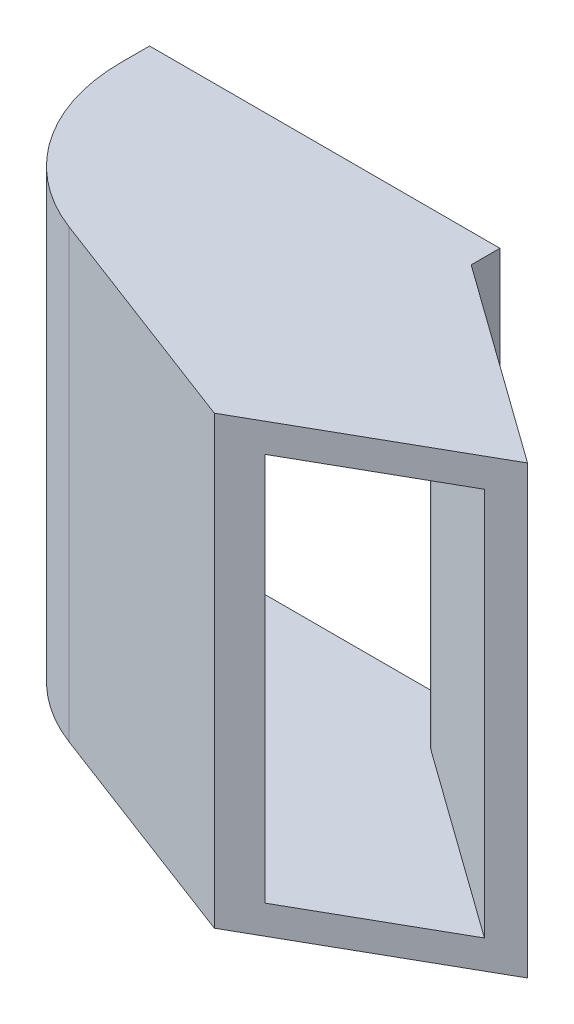
SolidWorks part; units mm, degrees
ref_plane "前基準面" through (0, 0, 0) normal (0, 0, 1) x (1, 0, 0)
ref_plane "上基準面" through (0, 0, 0) normal (0, 1, 0) x (1, 0, 0)
ref_plane "右基準面" through (0, 0, 0) normal (1, 0, 0) x (0, 0, -1)
sketch "草圖3" plane through (0, 0, 0) normal (0, 1, 0) x (1, 0, 0)
  line L0 (-1.5, 0) -> (16.8, 0)
  line L1 (0, 0) -> (15.3, 0) construction
  line L2 (4.5572, -8.7751) -> (16.8, -13.4178)
  line L4 (16.8, 0) -> (27.2341, -7.4907)
  line L5 (27.2341, -7.4907) -> (16.8, -13.4178)
  line L6 (22.0171, -10.4542) -> (31.038, -26.3351) construction
  arc A0 (-1.5, 0) -> (4.5572, -8.7751) centre (7.8849, 0) ccw
  point P6 (7.65, 0)
  dimension "D1" = 15.3
  dimension "D2" = 1.5
  dimension "D3" = 12
extrude "填料-伸長2" add sketch "草圖3" against normal blind 23.3
ref_plane "平面1" through (0, -1.5, 0) normal (0, 1, 0) x (1, 0, 0)
sketch "草圖4" plane through (0, -1.5, 0) normal (0, 1, 0) x (1, 0, 0)
  line L2 (26.3593, -8.7092) -> (15.9252, -1.2185)
  line L3 (25.7982, -8.3064) -> (15.9252, -1.2185)
  line L4 (0, 0) -> (15.3, 0)
  line L5 (5.0891, -7.3726) -> (17.3319, -12.0152)
  line L6 (5.0891, -7.3726) -> (18.4936, -12.4557)
  line L16 (27.2341, -7.4907) -> (16.8, -13.4178) construction
  line L18 (18.4936, -12.4557) -> (25.7982, -8.3064)
  arc A0 (15.3, 0) -> (15.9252, -1.2185) centre (16.8, 0) ccw
  arc A4 (0, 0) -> (5.0891, -7.3726) centre (7.8849, 0) ccw
  arc A5 (0, 0) -> (5.0891, -7.3726) centre (7.8849, 0) ccw
  dimension "D1" = 1.5
  dimension "D2" = 1.5
extrude "除料-伸長1" cut sketch "草圖4" against normal offset from surface (20.3 mm away) 1.5 up to face at (12.5048, -23.3, 6.1255)
sketch "草圖5" plane through (0, 0, 0) normal (0, 0, -1) x (-1, 0, 0)
  line L1 (-16.8, 0) -> (1.5, 0)
  line L2 (-16.8, 0) -> (-16.8, -23.3)
  line L3 (-16.8, -23.3) -> (1.5, -23.3)
  line L4 (1.5, 0) -> (1.5, -23.3)
  line L5 (-15.3, -1.5) -> (0, -1.5)
  line L6 (-15.3, -1.5) -> (-15.3, -21.8)
  line L7 (-15.3, -21.8) -> (0, -21.8)
  line L8 (0, -1.5) -> (0, -21.8)
extrude "填料-伸長3" add sketch "草圖5" along normal blind 1.5
